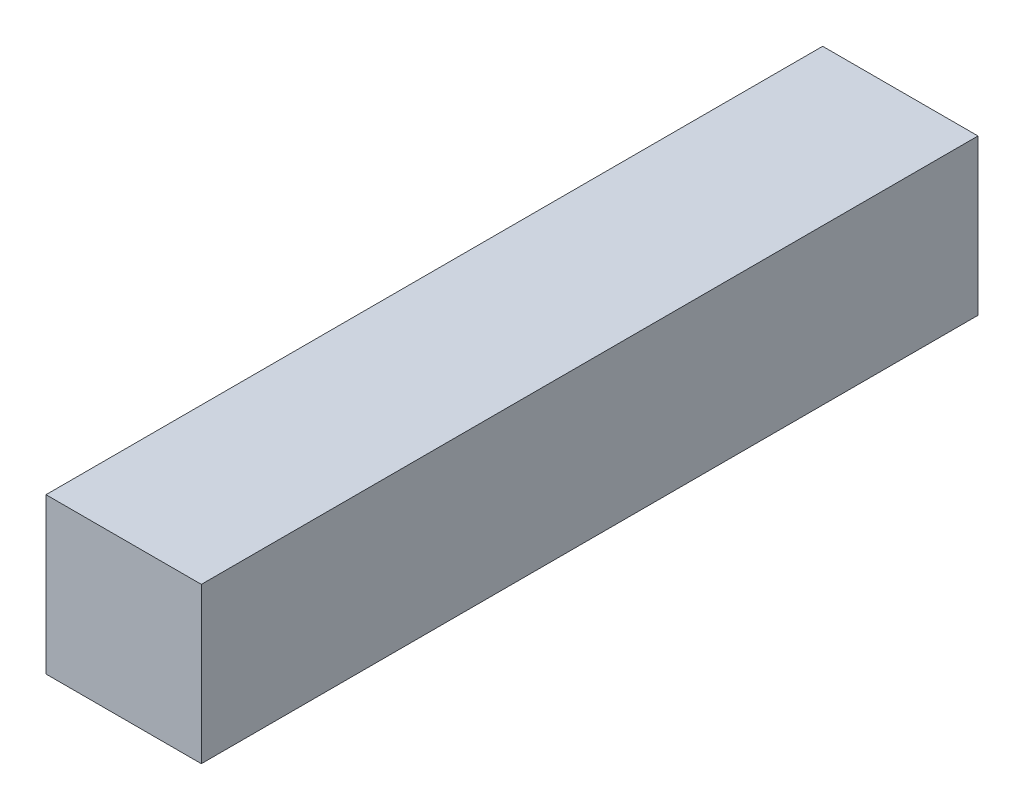
SolidWorks part; units mm, degrees
ref_plane "前视基准面" through (0, 0, 0) normal (0, 0, 1) x (1, 0, 0)
ref_plane "上视基准面" through (0, 0, 0) normal (0, 1, 0) x (1, 0, 0)
ref_plane "右视基准面" through (0, 0, 0) normal (1, 0, 0) x (0, 0, -1)
other "Configuration Table"
sketch "草图1" plane through (0, 0, 0) normal (0, 0, 1) x (1, 0, 0)
  line L1 (0, 0) -> (40000, 0)
  line L2 (0, 0) -> (0, 40000)
  line L3 (0, 40000) -> (40000, 40000)
  line L4 (40000, 0) -> (40000, 40000)
extrude "凸台-拉伸1" add sketch "草图1" against normal blind 200000
